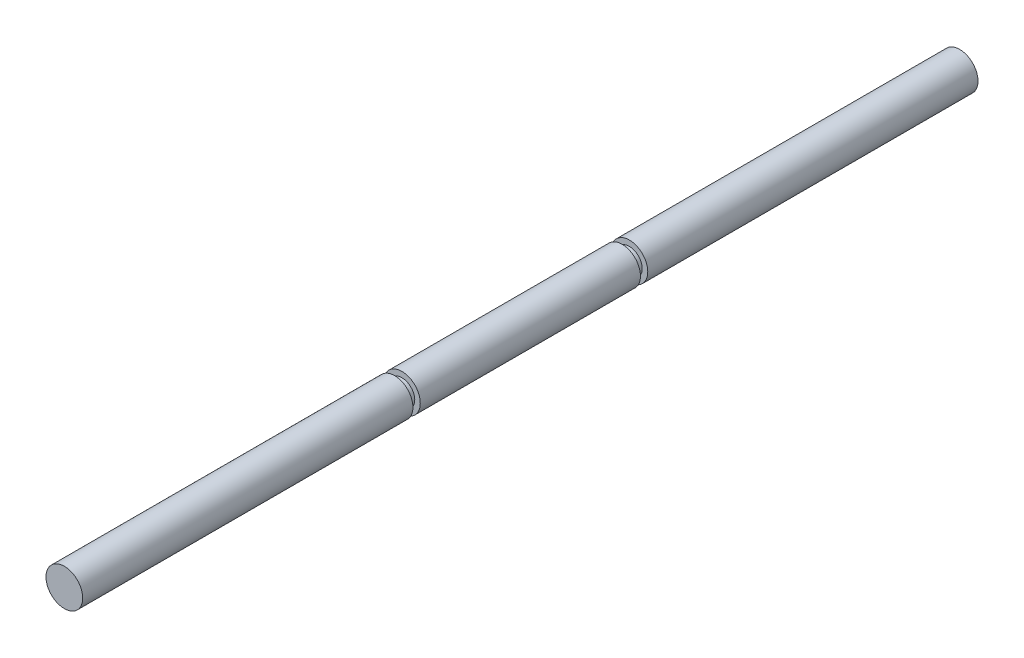
SolidWorks part; units mm, degrees
ref_plane "前视基准面" through (0, 0, 0) normal (0, 0, 1) x (1, 0, 0)
ref_plane "上视基准面" through (0, 0, 0) normal (0, 1, 0) x (1, 0, 0)
ref_plane "右视基准面" through (0, 0, 0) normal (1, 0, 0) x (0, 0, -1)
sketch "草图1" plane through (0, 0, 0) normal (0, 0, 1) x (1, 0, 0)
  circle A0 centre (0, 0) radius 5
  dimension "D1" = 10
extrude "凸台-拉伸1" add sketch "草图1" along normal blind 60
sketch "草图2" plane through (0, 0, 60) normal (0, 0, 1) x (1, 0, 0)
  circle A0 centre (0, 0) radius 3.5
  dimension "D1" = 7
extrude "凸台-拉伸2" add sketch "草图2" along normal blind 2
sketch "草图3" plane through (0, 0, 0) normal (0, 0, -1) x (-1, 0, 0)
  circle A0 centre (0, 0) radius 3.5
  dimension "D1" = 7
extrude "凸台-拉伸3" add sketch "草图3" along normal blind 2
sketch "草图4" plane through (0, 0, -2) normal (0, 0, -1) x (-1, 0, 0)
  circle A0 centre (0, 0) radius 5
  dimension "D1" = 10
extrude "凸台-拉伸4" add sketch "草图4" along normal blind 90
sketch "草图5" plane through (0, 0, 62) normal (0, 0, 1) x (1, 0, 0)
  circle A0 centre (0, 0) radius 5
  dimension "D1" = 10
extrude "凸台-拉伸5" add sketch "草图5" along normal blind 90
